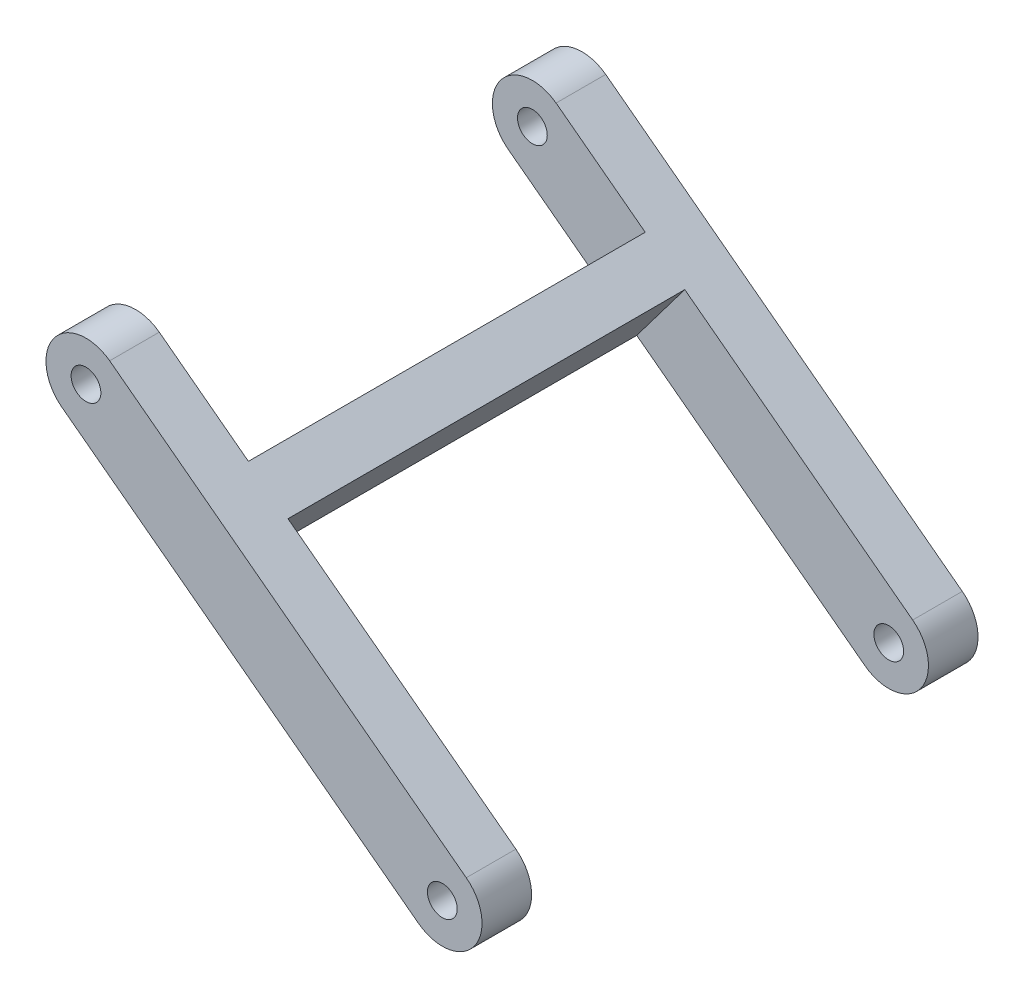
SolidWorks part; units mm, degrees
ref_plane "Plan de face" through (0, 0, 0) normal (0, 0, 1) x (1, 0, 0)
ref_plane "Plan de dessus" through (0, 0, 0) normal (0, 1, 0) x (1, 0, 0)
ref_plane "Plan de droite" through (0, 0, 0) normal (1, 0, 0) x (0, 0, -1)
sketch "Esquisse1" plane through (0, 0, 0) normal (0, 0, 1) x (1, 0, 0)
  line L0 (0, 0) -> (0, 13.0667) construction
  line L1 (2.4114, 3.1914) -> (-33.5323, 30.3499)
  line L2 (0, 0) -> (-35.923, 27.1023) construction
  line L3 (-2.4068, -3.1949) -> (-38.3895, 23.9119)
  line L4 (-35.923, 27.1023) -> (-33.5323, 30.3499) construction
  line L5 (-33.5323, 30.3499) -> (-38.3138, 23.8548) construction
  arc A4 (-2.4068, -3.1949) -> (2.4114, 3.1914) centre (0, 0) ccw
  arc A5 (-33.5323, 30.3499) -> (-38.3895, 23.9119) centre (-35.923, 27.1023) ccw
  circle A6 centre (-35.923, 27.1023) radius 1.5
  circle A7 centre (0, 0) radius 1.5
  point P14 (0, 0)
  dimension "D3" = 45
extrude "Boss.-Extru.1" add sketch "Esquisse1" along normal blind 5
sketch "Esquisse2" plane through (0, 0, 0) normal (0, 0, -1) x (-1, 0, 0)
  line L0 (35.923, 27.1023) -> (0, 0) construction
  line L1 (20.5609, 20.5489) -> (25.404, 14.1296)
  line L2 (-2.4114, 3.1914) -> (33.5323, 30.3499) construction
  line L5 (38.3895, 23.9119) -> (2.4068, -3.1949) construction
  line L6 (24.55, 23.563) -> (29.3974, 17.1379)
  line L7 (20.5609, 20.5489) -> (24.55, 23.563)
  line L8 (29.3974, 17.1379) -> (25.404, 14.1296)
  dimension "D3" = 90
extrude "Boss.-Extru.2" add sketch "Esquisse2" along normal blind 20
mirror "Symétrie1" about plane through (0, 0, -20) normal (0, 0, 1) of "Boss.-Extru.1", "Boss.-Extru.2"
